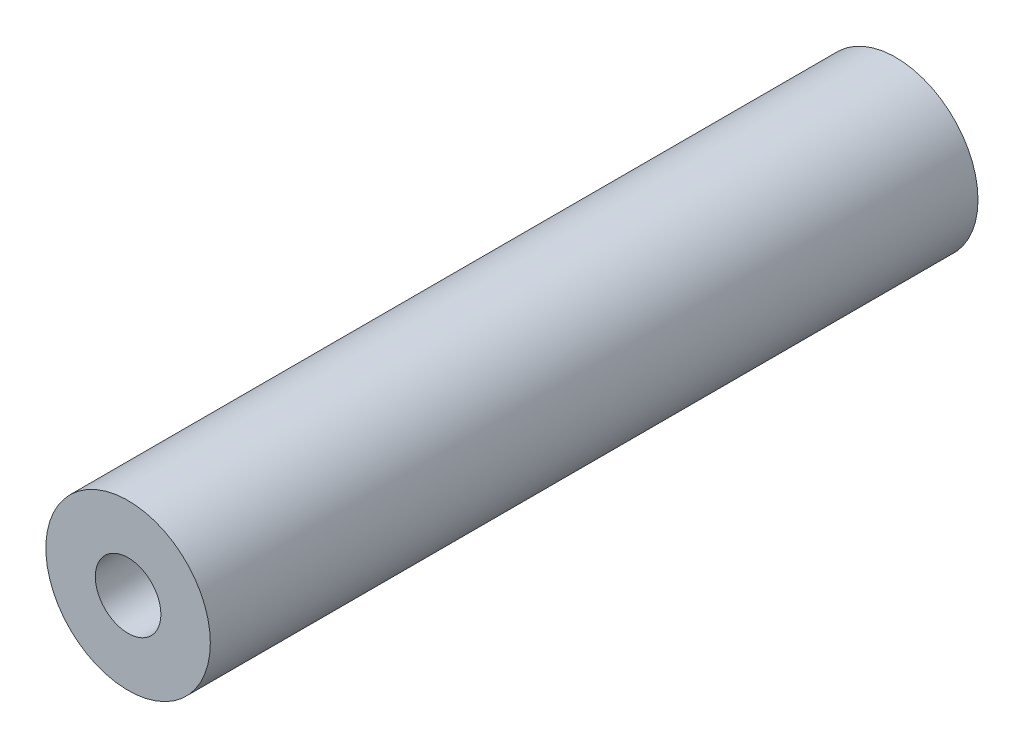
SolidWorks part; units mm, degrees
ref_plane "Front Plane" through (0, 0, 0) normal (0, 0, 1) x (1, 0, 0)
ref_plane "Top Plane" through (0, 0, 0) normal (0, 1, 0) x (1, 0, 0)
ref_plane "Right Plane" through (0, 0, 0) normal (1, 0, 0) x (0, 0, -1)
sketch "Sketch1" plane through (0, 0, 0) normal (0, 0, 1) x (1, 0, 0)
  circle A0 centre (0, 0) radius 4.7625
  dimension "D1" = 9.525
extrude "Boss-Extrude1" add sketch "Sketch1" along normal mid plane 44.45
hole_wizard "#10-24 Tapped Hole1" positions "3DSketch1" profile "Sketch2" tap size "#10-24" standard "ANSI Inch"
sketch3d "3DSketch1"
  line L0 (0, 0, 22.225) -> (0, 0, -22.225) construction
  point P0 (0, 0, 22.225)
  point P4 (0, 0, -22.225)
sketch "Sketch2" plane through (0, 0, 22.225) normal (1, 0, 0) x (0, -1, 0)
  line L0 (0, 0) -> (0, 14.0948)
  line L1 (0, 14.0948) -> (1.8986, 12.954)
  line L2 (1.8986, 12.954) -> (1.8986, 0)
  line L5 (1.8986, 0) -> (0, 0)
  line L10 (0, 14.0948) -> (-1.8986, 12.954) construction
  line L11 (0, -6.35) -> (0, 107.95) construction
  dimension "Tap Drill Dia." = 3.7973
  dimension "Tap Drill Depth" = 12.954
  dimension "Drill Angle" = 118
